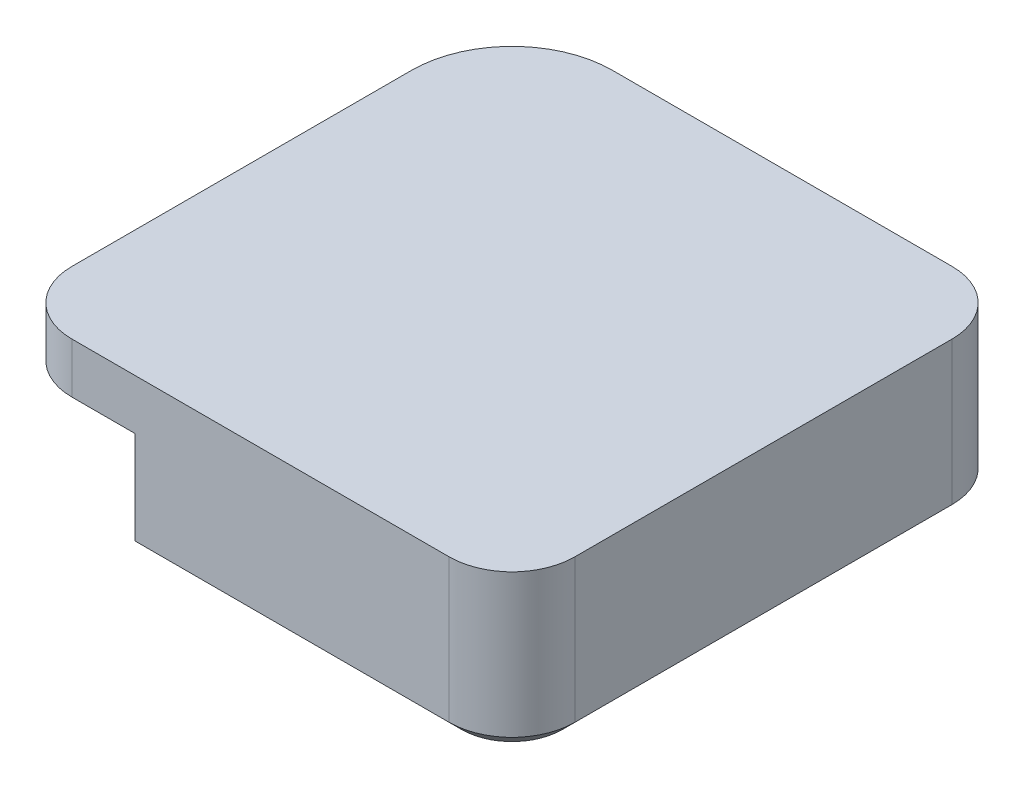
SolidWorks part; units mm, degrees
ref_plane "Front Plane" through (0, 0, 0) normal (0, 0, 1) x (1, 0, 0)
ref_plane "Top Plane" through (0, 0, 0) normal (0, 1, 0) x (1, 0, 0)
ref_plane "Right Plane" through (0, 0, 0) normal (1, 0, 0) x (0, 0, -1)
sketch "Sketch1" plane through (0, 0, 0) normal (0, 1, 0) x (1, 0, 0)
  line L0 (5, 0) -> (0, 5)
  line L1 (0, 0) -> (17.5, 0)
  line L2 (0, 0) -> (0, 16)
  line L3 (4, 20) -> (17.5, 20)
  line L4 (20, 2.5) -> (20, 17.5)
  arc A0 (20, 2.5) -> (17.5, 0) centre (17.5, 2.5) cw
  arc A1 (20, 17.5) -> (17.5, 20) centre (17.5, 17.5) ccw
  arc A2 (4, 20) -> (0, 16) centre (4, 16) ccw
  circle A3 centre (4, 16) radius 1.75
  circle A4 centre (10, 16) radius 1.8
  circle A5 centre (16, 16) radius 1.85
  circle A6 centre (4, 10) radius 1.9
  circle A7 centre (10, 10) radius 1.95
  circle A8 centre (16, 10) radius 2
  circle A10 centre (10, 4) radius 2.05
  circle A11 centre (16, 4) radius 2.1
  point P9 (20, 0)
  point P14 (0, 20)
  point P24 (0, 0)
  point P25 (0, 0)
  point P32 (0, 0)
  point P33 (0, 0)
  point P34 (0, 0)
  point P35 (0, 0)
  point P36 (0, 0)
  point P37 (0, 0)
  point P38 (0, 0)
  dimension "D4" = 2.5
  dimension "D5" = 3.5
  dimension "D6" = 3.6
  dimension "D7" = 3.7
  dimension "D8" = 3.8
  dimension "D9" = 3.9
  dimension "D10" = 4
  dimension "D11" = 16
  dimension "D12" = 4.1
  dimension "D13" = 4.2
  dimension "D1" = 20
  dimension "D2" = 20
  dimension "D3" = 5
  dimension "5" = 5
  dimension "D14" = 4
  dimension "D15" = 10
  dimension "D16" = 16
  dimension "D17" = 4
  dimension "D18" = 10
extrude "Boss-Extrude1" add sketch "Sketch1" along normal blind 4.2 contours L3 A2 L2 L0 L1 A0 L4 A1 A11 A10 A8 A7 A6 A5 A4 A3
sketch "Sketch2" plane through (0, 4.2, 0) normal (0, 1, 0) x (1, 0, 0)
  line L2 (20, 17.5) -> (20, 2.5)
  line L3 (17.5, 0) -> (2.5, 0)
  line L5 (20, 2.5) -> (20, 17.5) construction
  line L6 (0, 5) -> (0, 16) construction
  line L7 (4, 20) -> (17.5, 20) construction
  line L8 (0, 5) -> (0, 16)
  line L9 (4, 20) -> (17.5, 20)
  line L10 (0, 2.5) -> (0, 5)
  arc A0 (0, 2.5) -> (2.5, 0) centre (2.5, 2.5) ccw
  arc A1 (17.5, 0) -> (20, 2.5) centre (17.5, 2.5) ccw
  arc A3 (17.5, 20) -> (20, 17.5) centre (17.5, 17.5) cw
  arc A4 (4, 20) -> (0, 16) centre (4, 16) ccw construction
  arc A5 (4, 20) -> (0, 16) centre (4, 16) ccw
  point P11 (0, 0)
  dimension "D1" = 2.5
extrude "Boss-Extrude2" add sketch "Sketch2" along normal blind 2
chamfer "Chamfer1" distance 0.5 angle 45 16 edges at (1.1716, 0, -18.8284) (0, 0, -10.5) (2.5, 0, -2.5) (11.25, 0, 0) (19.2678, 0, -0.7322) (20, 0, -10) (19.2678, 0, -19.2678) (10.75, 0, -20) (4, 0, -14.25) (10, 0, -14.2) (16, 0, -14.15) (4, 0, -8.1) (10, 0, -8.05) (16, 0, -8) (10, 0, -1.95) (16, 0, -1.9)
